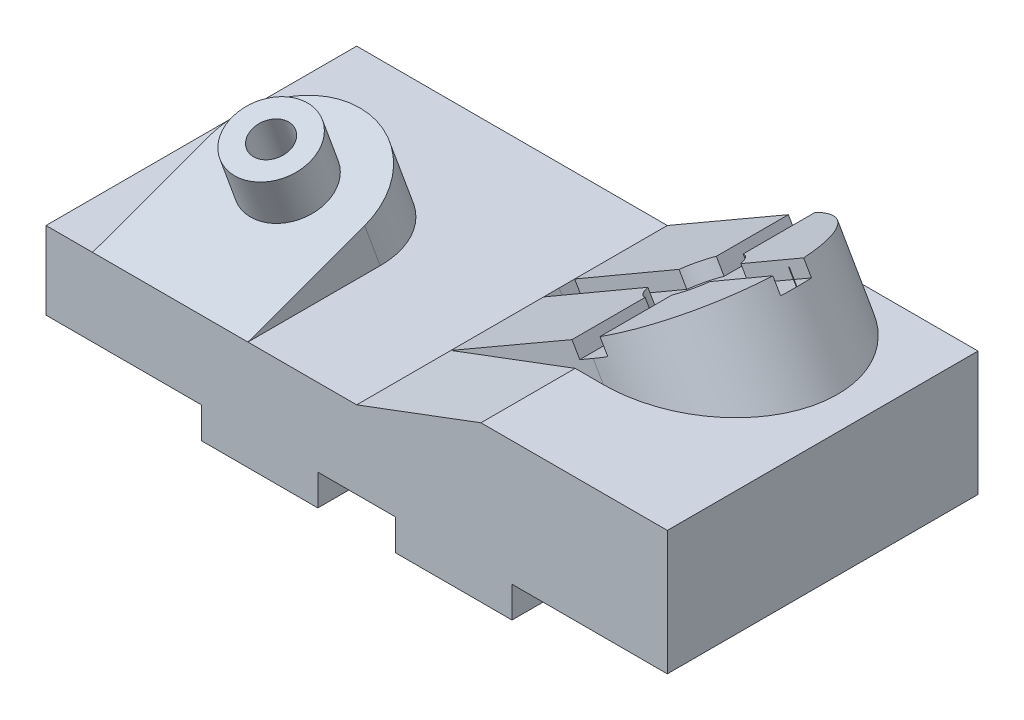
SolidWorks part; units mm, degrees
ref_plane "Front Plane" through (0, 0, 0) normal (0, 0, 1) x (1, 0, 0)
ref_plane "Top Plane" through (0, 0, 0) normal (0, 1, 0) x (1, 0, 0)
ref_plane "Right Plane" through (0, 0, 0) normal (1, 0, 0) x (0, 0, -1)
sketch "Sketch1" plane through (0, 0, 0) normal (0, 0, 1) x (1, 0, 0)
  line L0 (-177.7778, 0) -> (-127.7778, 0)
  line L1 (-127.7778, 0) -> (-127.7778, -10)
  line L2 (-127.7778, -10) -> (-90.2778, -10)
  line L3 (-90.2778, -10) -> (-90.2778, 0)
  line L4 (-90.2778, 0) -> (-65.2778, 0)
  line L5 (-65.2778, 0) -> (-65.2778, -10)
  line L6 (-65.2778, -10) -> (-27.7778, -10)
  line L7 (-27.7778, -10) -> (-27.7778, 0)
  line L8 (-27.7778, 0) -> (22.2222, 0)
  line L9 (22.2222, 0) -> (22.2222, 40)
  line L10 (22.2222, 40) -> (-37.7778, 40)
  line L11 (-37.7778, 40) -> (-77.7778, 25)
  line L12 (-77.7778, 25) -> (-177.7778, 25)
  line L13 (-177.7778, 0) -> (-177.7778, 25)
  line L14 (-177.7778, 0) -> (-178.3889, 0.6041)
  dimension "D1" = 50
  dimension "D2" = 37.5
  dimension "D3" = 25
  dimension "D4" = 10
  dimension "D5" = 200
  dimension "D6" = 100
  dimension "D7" = 40
  dimension "D8" = 60
  dimension "D9" = 25
  dimension "D10" = 100
extrude "Boss-Extrude1" add sketch "Sketch1" along normal blind 100 contours L13 L0 L1 L2 L3 L4 L5 L6 L7 L8 L9 L10 L11 L12
ref_plane "Plane3" through (0, 54.2149, 19.7326) normal (0, 0.9397, 0.342) x (-1, 0, 0)
sketch "Sketch5" plane through (0, 54.2149, 19.7326) normal (0, 0.9397, 0.342) x (-1, 0, 0)
  line L0 (112.7778, 85.4188) -> (112.7778, 45.4188)
  line L1 (77.7778, 85.4188) -> (177.7778, 85.4188) construction
  line L2 (162.7778, 45.4188) -> (162.7778, 85.4188)
  line L3 (162.7778, 85.4188) -> (162.7778, 45.4188)
  line L4 (162.7778, 85.4188) -> (112.7778, 85.4188)
  arc A0 (112.7778, 45.4188) -> (162.7778, 45.4188) centre (137.7778, 45.4188) ccw
  dimension "D1" = 15
  dimension "D2" = 50
  dimension "D3" = 40
extrude "Boss-Extrude2" add sketch "Sketch5" against normal up to next contours L0 A0 L2 L4
sketch "Sketch6" plane through (0, 54.2149, 19.7326) normal (0, 0.9397, 0.342) x (1, 0, 0)
  circle A0 centre (-137.7778, -45.4188) radius 12.5
  circle A1 centre (-137.7778, -45.4188) radius 6
  dimension "D1" = 25
  dimension "D2" = 12
extrude "Boss-Extrude4" add sketch "Sketch6" along normal blind 15
sketch "Sketch7" plane through (0, 54.2149, 19.7326) normal (0, 0.9397, 0.342) x (1, 0, 0)
  circle A0 centre (-137.7778, -45.4188) radius 6
  dimension "D1" = 12
extrude "Cut-Extrude3" cut sketch "Sketch7" against normal through all
ref_plane "Plane4" through (-30.2698, 52.4288, 0) normal (-0.5, 0.866, 0) x (0, 0, -1)
sketch "Sketch10" plane through (-30.2698, 52.4288, 0) normal (-0.5, 0.866, 0) x (0, 0, -1)
  line L0 (0, 54.8575) -> (-69.6613, 54.8575)
  line L1 (-100, 54.8575) -> (0, 54.8575) construction
  line L2 (-69.6613, 54.8575) -> (-69.6613, 4.8575)
  line L3 (0, 54.8575) -> (-69.6613, 54.8575)
  line L4 (0, 0) -> (0, 54.8575)
  arc A0 (-69.6613, 4.8575) -> (0, 0) centre (-34.6613, 4.8575) ccw
  dimension "D2" = 35
  dimension "D1" = 50
extrude "Boss-Extrude10" add sketch "Sketch10" against normal up to next contours L2 A0 L4 L0
sketch "Sketch11" plane through (-30.2698, 52.4288, 0) normal (-0.5, 0.866, 0) x (0.866, 0.5, 0)
  line L0 (-54.8575, -34.8306) -> (30.1413, -34.3803) construction
  line L1 (-54.8575, 0) -> (-54.8575, -69.6613) construction
  line L2 (-4.8575, -69.6613) -> (-4.8575, 0) construction
  line L3 (0, 0) -> (-54.8575, 0) construction
  line L4 (-54.831, -39.8306) -> (-16.3291, -39.6266)
  line L5 (0.1425, -69.6613) -> (0.1425, -46.1177)
  line L6 (-54.884, -29.8307) -> (-16.2986, -29.6263)
  line L7 (-9.8575, -69.6613) -> (-9.8575, -46.1177)
  line L8 (6.5296, -29.5053) -> (30.1148, -29.3803)
  line L9 (-54.884, -29.8307) -> (30.1148, -29.3803) construction
  line L10 (0.1425, -23.2048) -> (0.1425, 0)
  line L11 (0.1425, -69.6613) -> (0.1425, 0) construction
  line L12 (-9.8575, -23.2048) -> (-9.8575, 0)
  line L13 (-9.8575, -69.6613) -> (-9.8575, 0) construction
  line L14 (6.666, -39.5047) -> (30.1678, -39.3802)
  line L15 (-54.831, -39.8306) -> (30.1678, -39.3802) construction
  line L16 (-54.884, -29.8307) -> (-54.831, -39.8306)
  line L17 (0.1425, -69.6613) -> (-9.8575, -69.6613)
  line L18 (30.1148, -29.3803) -> (30.1678, -39.3802)
  line L19 (30.1678, -39.3802) -> (30.1673, -39.329)
  line L20 (0.1425, 0) -> (-9.8575, 0)
  arc A0 (-9.8575, -23.2048) -> (-16.2986, -29.6263) centre (-4.8575, -34.6613) ccw
  arc A1 (-4.8575, -69.6613) -> (0, 0) centre (-4.8575, -34.6613) ccw construction
  arc A2 (-4.8575, -69.6613) -> (0, 0) centre (-4.8575, -34.6613) ccw construction
  arc A3 (-16.3291, -39.6266) -> (-9.8575, -46.1177) centre (-4.8575, -34.6613) ccw
  arc A4 (0.1425, -46.1177) -> (6.666, -39.5047) centre (-4.8575, -34.6613) ccw
  arc A5 (6.5296, -29.5053) -> (0.1425, -23.2048) centre (-4.8575, -34.6613) ccw
  line M1 (-54.8575, -69.6613) -> (-4.8575, -69.6613)
  arc M2 (-4.8575, -69.6613) -> (0, 0) centre (-4.8575, -34.6613) ccw
  line M3 (0, 0) -> (-54.8575, 0)
  line M4 (-54.8575, 0) -> (-54.8575, -69.6613)
  dimension "D3" = 25
  dimension "D4" = 10
  dimension "D1" = 5
  dimension "D2" = 5
extrude "Cut-Extrude6" cut sketch "Sketch11" against normal blind 5 contours L8 A5 L10 L12 A0 L6 L16 L4 A3 L7 L5 A4 L14 L18 M2 M3 M4 M1
